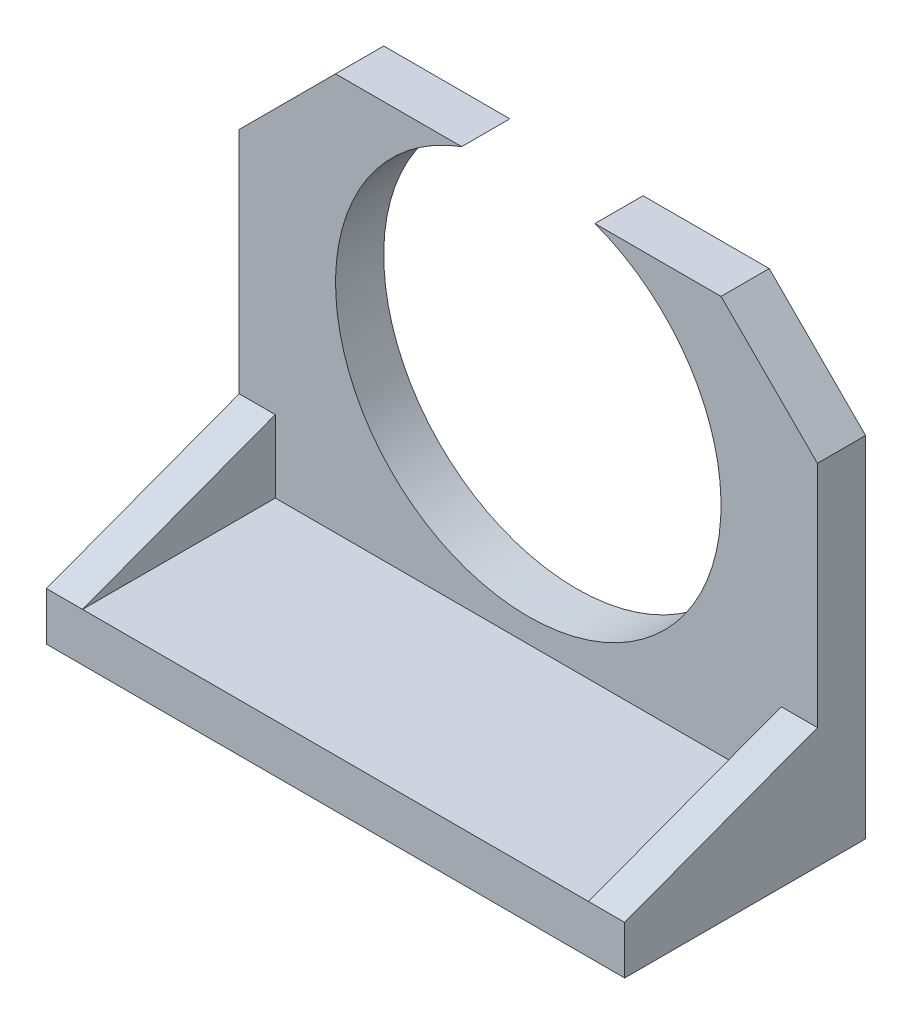
SolidWorks part; units mm, degrees
ref_plane "Front Plane" through (0, 0, 0) normal (0, 0, 1) x (1, 0, 0)
ref_plane "Top Plane" through (0, 0, 0) normal (0, 1, 0) x (1, 0, 0)
ref_plane "Right Plane" through (0, 0, 0) normal (1, 0, 0) x (0, 0, -1)
sketch "Sketch1" plane through (0, 0, 0) normal (0, 1, 0) x (1, 0, 0)
  line L1 (-12, 5) -> (12, 5)
  line L2 (-12, 5) -> (-12, -5)
  line L3 (-12, -5) -> (12, -5)
  line L4 (12, 5) -> (12, -5)
  line L5 (-12, 5) -> (12, -5) construction
  line L6 (-12, -5) -> (12, 5) construction
  point P0 (0, 0)
  dimension "D1" = 10
  dimension "D2" = 24
extrude "Boss-Extrude1" add sketch "Sketch1" along normal blind 2
sketch "Sketch2" plane through (0, 2, 0) normal (0, 1, 0) x (1, 0, 0)
  line L0 (12, -5) -> (12, 5) construction
  line L1 (-12, 5) -> (12, 5)
  line L2 (-12, 5) -> (-12, 3)
  line L3 (-12, 3) -> (12, 3)
  line L4 (12, 5) -> (12, 3)
  dimension "D1" = 2
extrude "Boss-Extrude2" add sketch "Sketch2" along normal blind 16.5
sketch "Sketch3" plane through (0, 0, -3) normal (0, 0, 1) x (1, 0, 0)
  line L0 (0, 18.5) -> (0, 2) construction
  line L1 (-12, 18.5) -> (12, 18.5) construction
  line L2 (-12, 2) -> (12, 2) construction
  circle A1 centre (0, 10.9928) radius 8
  dimension "D1" = 16
extrude "Cut-Extrude1" cut sketch "Sketch3" against normal blind 2
sketch "Sketch6" plane through (0, 0, -3) normal (0, 0, 1) x (1, 0, 0)
  line L0 (-12, 18.5) -> (-8, 18.5)
  line L1 (-12, 18.5) -> (-2.7644, 18.5) construction
  line L2 (-8, 18.5) -> (-12, 14.5)
  line L3 (-12, 18.5) -> (-12, 2) construction
  line L4 (-12, 14.5) -> (-12, 18.5)
  line L5 (12, 18.5) -> (8, 18.5)
  line L6 (12, 18.5) -> (12, 2) construction
  line L7 (2.7644, 18.5) -> (12, 18.5) construction
  line L8 (8, 18.5) -> (12, 14.5)
  line L9 (12, 14.5) -> (12, 18.5)
  dimension "D1" = 4
extrude "Cut-Extrude2" cut sketch "Sketch6" against normal blind 2
sketch "Sketch7" plane through (-12, 0, 0) normal (-1, 0, 0) x (0, 0, 1)
  line L0 (-3, 2) -> (-3, 5)
  line L1 (-3, 14.5) -> (-3, 2) construction
  line L2 (-3, 5) -> (5, 2)
  line L3 (5, 2) -> (-3, 2)
  dimension "D1" = 3
extrude "Boss-Extrude4" add sketch "Sketch7" against normal blind 1.5
sketch "Sketch8" plane through (12, 0, 0) normal (1, 0, 0) x (0, 0, -1)
  line L0 (-5, 2) -> (3, 2)
  line L1 (3, 2) -> (3, 5)
  line L2 (3, 14.5) -> (3, 2) construction
  line L3 (3, 5) -> (-5, 2)
  dimension "D1" = 3
extrude "Boss-Extrude5" add sketch "Sketch8" against normal blind 1.5
